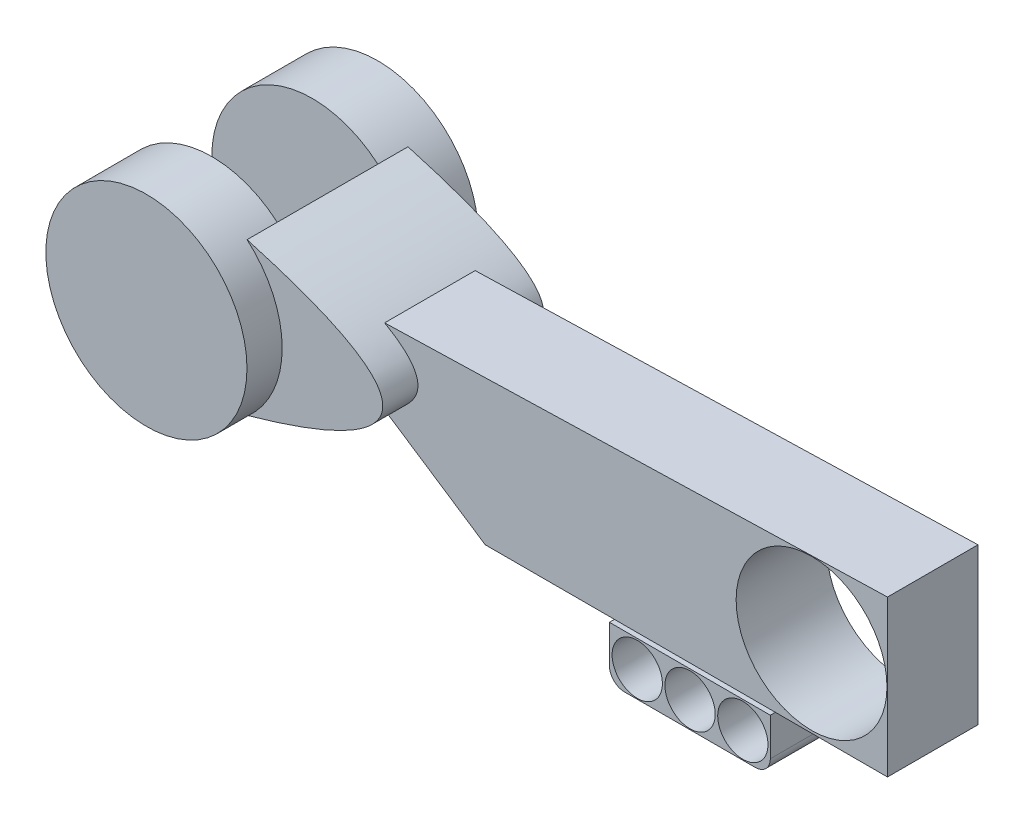
SolidWorks part; units mm, degrees
material "PBTP"
ref_plane "Спереди" through (0, 0, 0) normal (0, 0, 1) x (1, 0, 0)
ref_plane "Сверху" through (0, 0, 0) normal (0, 1, 0) x (1, 0, 0)
ref_plane "Справа" through (0, 0, 0) normal (1, 0, 0) x (0, 0, -1)
sketch "Sketch1" plane through (0, 0, 0) normal (0, 0, 1) x (1, 0, 0)
  circle A0 centre (0, 0) radius 2
  dimension "D1" = 4
extrude "Boss-Extrude1" add sketch "Sketch1" along normal blind 0.1 and the other way blind 1.2
sketch "Sketch2" plane through (0, 0, -1.2) normal (0, 0, -1) x (-1, 0, 0)
  circle A0 centre (0, 0) radius 2 construction
  circle A1 centre (0, 0) radius 2 construction
  circle A2 centre (0, 0) radius 2
  arc A3 (-1.3019, 1.5182) -> (-1.3195, -1.5029) centre (0, 0) ccw
  spline S0 degree 2 poles (-1.3019, 1.5182) (-6.6893, 0.0036) (-1.3195, -1.5029) knots 0 0 0 1 1 1
  dimension "D2" = 4
  dimension "D1" = 0
extrude "Boss-Extrude2" add sketch "Sketch2" against normal blind 0.6 and the other way blind 1
sketch "Sketch3" plane through (0, 0, -2.2) normal (0, 0, -1) x (-1, 0, 0)
  line L0 (-3.3375, -0.7461) -> (-5.3375, -2.0685)
  line L1 (-5.3375, -2.0685) -> (-13.3375, -2.0685)
  line L2 (-13.3375, 1.0315) -> (-3.3375, 0.7534)
  line L3 (-13.3375, -2.0685) -> (-13.3375, 1.0315)
  parabola Q0 (-1.3019, 1.5182) -> (-1.3195, -1.5029) focus (-3.7879, 0.003) apex (-4, 0.0028) construction
  parabola Q2 (-1.3019, 1.5182) -> (-1.3195, -1.5029) focus (-3.7879, 0.003) apex (-4, 0.0028) construction
  spline M3 degree 2 poles (-1.3019, 1.5182) (-6.6893, 0.0036) (-1.3195, -1.5029) knots 0 0 0 1 1 1
  dimension "D1" = 8
  dimension "D2" = 2
  dimension "D3" = 10
  dimension "D4" = 3.1
extrude "Boss-Extrude3" add sketch "Sketch3" against normal blind 0.9 contours L3 L1 L0 L2 M3
sketch "Sketch6" plane through (0, 0, -1.3) normal (0, 0, 1) x (1, 0, 0)
  line L0 (13.3375, 1.0315) -> (3.3375, 0.7534) construction
  line L3 (13.3375, -2.0685) -> (13.3375, 1.0315) construction
  circle A0 centre (11.8275, -0.5211) radius 1.5
  dimension "D1" = 1.51
  dimension "D2" = 1.51
extrude "Cut-Extrude13" cut sketch "Sketch6" against normal mid plane 5
ref_plane "Plane1" through (0, 0, 0.1) normal (0, 0, 1) x (1, 0, 0)
ref_plane "Plane2" through (0, 0, -2.2) normal (0, 0, -1) x (-1, 0, 0)
sketch "Sketch8" plane through (0, 0, -2.2) normal (0, 0, -1) x (-1, 0, 0)
  line L0 (-13.3375, 1.0315) -> (-13.3375, -2.0685)
  line L1 (-13.3375, -2.0685) -> (-5.3375, -2.0685)
  line L2 (-5.3375, -2.0685) -> (-3.3375, -0.7461)
  line L3 (-3.3375, -0.7461) -> (-3.3375, 0.7534)
  line L4 (-3.3375, 0.7534) -> (-13.3375, 1.0315)
mirror "Mirror2" about plane through (0, 0, -2.2) normal (0, 0, -1) of "Boss-Extrude1", "Boss-Extrude3", "Boss-Extrude2"
mirror "Mirror3" about plane through (0, 0, -2.2) normal (0, 0, -1) of "Boss-Extrude1"
mirror "Mirror4" about plane through (0, 0, -2.2) normal (0, 0, -1) of "Cut-Extrude13"
ref_plane "Plane3" through (0, 0, -3.2) normal (0, 0, -1) x (-1, 0, 0)
sketch "Sketch9" plane through (0, 0, -3.2) normal (0, 0, -1) x (-1, 0, 0)
  line L0 (-5.3375, -2.0685) -> (-13.3375, -2.0685) construction
  line L1 (-11.1075, -2.0685) -> (-7.9075, -2.0685)
  line L2 (-11.1075, -2.0685) -> (-11.1075, -2.8185)
  line L3 (-10.8075, -3.1185) -> (-8.2075, -3.1185)
  line L4 (-7.9075, -2.0685) -> (-7.9075, -2.8185)
  circle A0 centre (-10.5609, -2.6017) radius 0.5
  circle A1 centre (-9.5109, -2.6017) radius 0.5
  circle A2 centre (-8.4609, -2.6017) radius 0.5
  arc A3 (-8.2075, -3.1185) -> (-7.9075, -2.8185) centre (-8.2075, -2.8185) ccw
  arc A4 (-11.1075, -2.8185) -> (-10.8075, -3.1185) centre (-10.8075, -2.8185) ccw
  dimension "D1" = 3
  dimension "D2" = 0.3
extrude "Boss-Extrude4" add sketch "Sketch9" along normal blind 0.0001 and the other way blind 2
